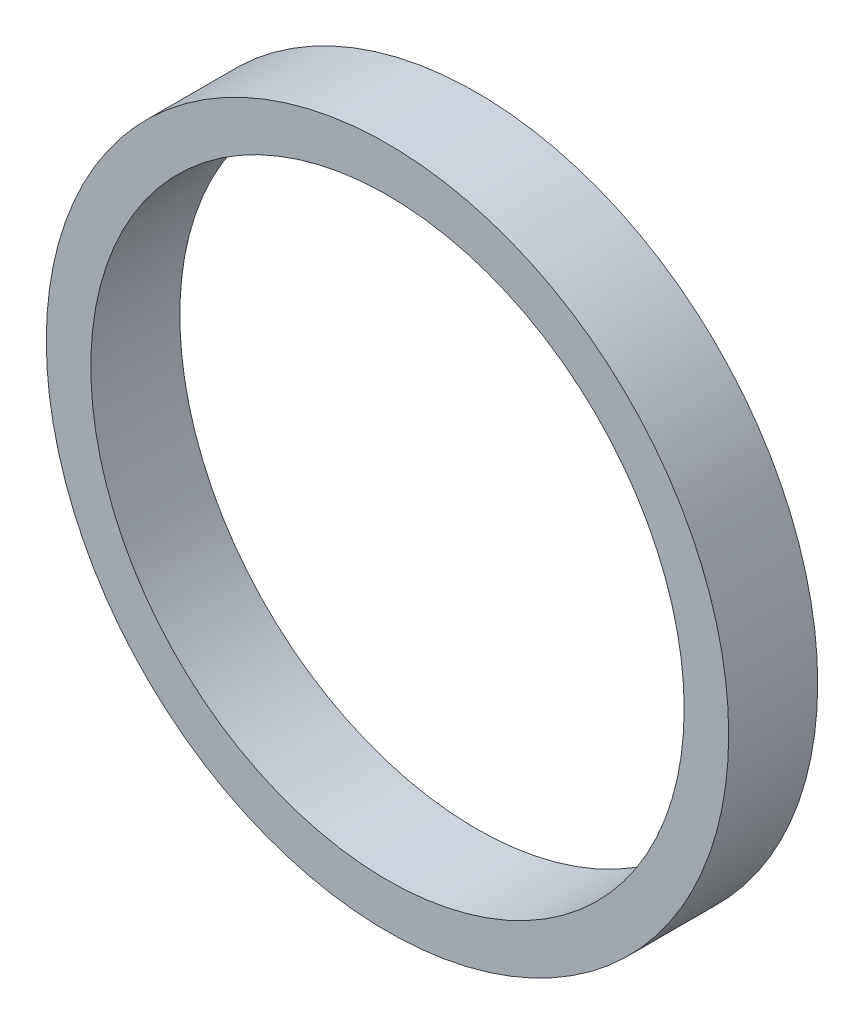
SolidWorks part; units mm, degrees
ref_plane "前视基准面" through (0, 0, 0) normal (0, 0, 1) x (1, 0, 0)
ref_plane "上视基准面" through (0, 0, 0) normal (0, 1, 0) x (1, 0, 0)
ref_plane "右视基准面" through (0, 0, 0) normal (1, 0, 0) x (0, 0, -1)
sketch "草图1" plane through (0, 0, 0) normal (0, 0, 1) x (1, 0, 0)
  circle A0 centre (0, 0) radius 10
  circle A1 centre (0, 0) radius 11.5
  dimension "D1" = 20
  dimension "D2" = 23
extrude "凸台-拉伸1" add sketch "草图1" along normal mid plane 3
